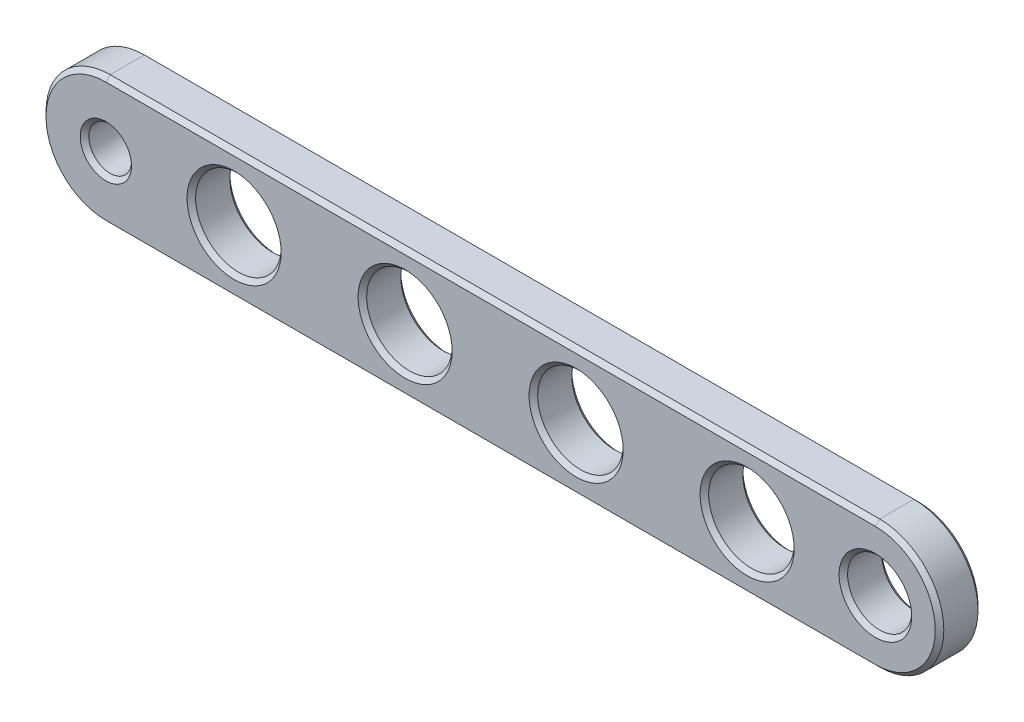
SolidWorks part; units mm, degrees
ref_plane "Front Plane" through (0, 0, 0) normal (0, 0, 1) x (1, 0, 0)
ref_plane "Top Plane" through (0, 0, 0) normal (0, 1, 0) x (1, 0, 0)
ref_plane "Right Plane" through (0, 0, 0) normal (1, 0, 0) x (0, 0, -1)
sketch "Sketch1" plane through (0, 0, 0) normal (0, 0, 1) x (1, 0, 0)
  line L0 (-18, 0) -> (18, 0) construction
  line L1 (-18, 3) -> (18, 3)
  line L2 (-18, -3) -> (18, -3)
  arc A0 (-18, 3) -> (-18, -3) centre (-18, 0) ccw
  arc A1 (18, -3) -> (18, 3) centre (18, 0) ccw
  circle A2 centre (-18, 0) radius 1
  circle A3 centre (18, 0) radius 1.5
  circle A4 centre (12, 0) radius 2
  circle A5 centre (4, 0) radius 2
  circle A6 centre (-4, 0) radius 2
  circle A7 centre (-12, 0) radius 2
  point P2 (0, 0)
  dimension "D2" = 3
  dimension "D3" = 2
  dimension "D4" = 3
  dimension "D5" = 4
  dimension "D6" = 6
  dimension "D1" = 36
  dimension "D7" = 8
  dimension "D8" = 8
  dimension "D9" = 6
  dimension "D10" = 8
extrude "Boss-Extrude1" add sketch "Sketch1" along normal blind 2
chamfer "Chamfer3" distance 0.2 angle 45 20 edges at (-10, 0, 0) (-2, 0, 0) (6, 0, 0) (14, 0, 0) (19.5, 0, 0) (-17, 0, 0) (0, -3, 0) (21, 0, 0) (0, 3, 0) (-21, 0, 0) (-10, 0, 2) (6, 0, 2) (19.5, 0, 2) (0, 3, 2) (21, 0, 2) (0, -3, 2) (-21, 0, 2) (-17, 0, 2) (14, 0, 2) (-2, 0, 2)
